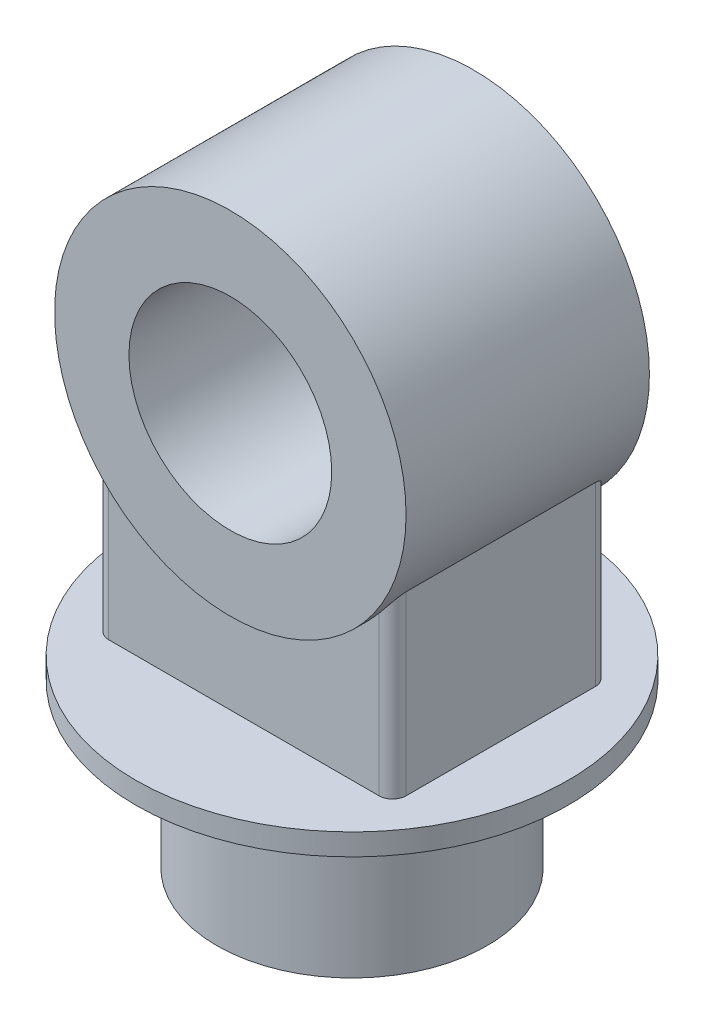
SolidWorks part; units mm, degrees
ref_plane "Front Plane" through (0, 0, 0) normal (0, 0, 1) x (1, 0, 0)
ref_plane "Top Plane" through (0, 0, 0) normal (0, 1, 0) x (1, 0, 0)
ref_plane "Right Plane" through (0, 0, 0) normal (1, 0, 0) x (0, 0, -1)
sketch "Sketch5" plane through (0, 0, 0) normal (0, 1, 0) x (1, 0, 0)
  circle A0 centre (0, 0) radius 100
extrude "Boss-Extrude1" add sketch "Sketch5" along normal blind 120
sketch "Sketch6" plane through (0, 120, 0) normal (0, 1, 0) x (1, 0, 0)
  circle A0 centre (0, 0) radius 160
extrude "Boss-Extrude2" add sketch "Sketch6" along normal blind 16
sketch "Sketch7" plane through (0, 0, 0) normal (0, 0, 1) x (1, 0, 0)
  line L0 (160, 136) -> (-160, 136) construction
  circle A0 centre (0, 336) radius 75
  circle A1 centre (0, 336) radius 130
  dimension "D1" = 150
  dimension "D2" = 260
  dimension "D3" = 200
extrude "Boss-Extrude3" add sketch "Sketch7" along normal mid plane 180 separate body
sketch "Sketch8" plane through (0, 136, 0) normal (0, 1, 0) x (1, 0, 0)
  line L1 (110, 80) -> (-110, 80)
  line L2 (110, 80) -> (110, -80)
  line L3 (110, -80) -> (-110, -80)
  line L4 (-110, 80) -> (-110, -80)
  line L5 (110, 80) -> (-110, -80) construction
  line L6 (110, -80) -> (-110, 80) construction
  point P0 (0, 0)
  dimension "D1" = 160
  dimension "D2" = 220
extrude "Boss-Extrude4" add sketch "Sketch8" along normal up to next
fillet "Fillet1" radius 10 2 edges at (-110, 201.359, 80) (110, 201.359, 80)
fillet "Fillet2" radius 10 2 edges at (110, 201.359, -80) (-110, 201.359, -80)
